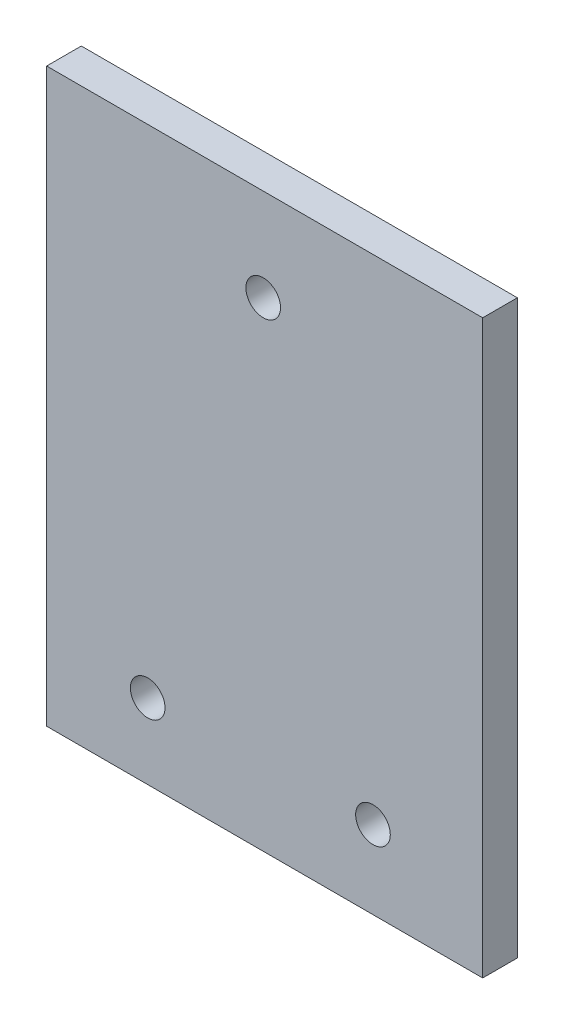
SolidWorks part; units mm, degrees
ref_plane "Front Plane" through (0, 0, 0) normal (0, 0, 1) x (1, 0, 0)
ref_plane "Top Plane" through (0, 0, 0) normal (0, 1, 0) x (1, 0, 0)
ref_plane "Right Plane" through (0, 0, 0) normal (1, 0, 0) x (0, 0, -1)
sketch "Sketch1" plane through (0, 0, 0) normal (0, 0, 1) x (1, 0, 0)
  line L1 (0, 0) -> (151, 0)
  line L2 (0, 0) -> (0, -198)
  line L3 (0, -198) -> (151, -198)
  line L4 (151, 0) -> (151, -198)
  dimension "D1" = 198
  dimension "D2" = 151
extrude "Boss-Extrude1" add sketch "Sketch1" along normal blind 12
sketch "Sketch2" plane through (0, 0, 12) normal (0, 0, 1) x (1, 0, 0)
  line L0 (151, -198) -> (151, 0) construction
  circle A0 centre (75, -32) radius 6
  circle A1 centre (35, -172) radius 6
  circle A2 centre (113, -171) radius 6
  point P6 (31.226, -162.6439)
  point P7 (0, 0)
  point P8 (35.6874, -160.818)
  point P14 (0, 0)
  point P16 (81.7441, 17.8722)
  dimension "D1" = 35
  dimension "D7" = 12
  dimension "D2" = 26
  dimension "D3" = 38
  dimension "D4" = 27
  dimension "D5" = 32
  dimension "D6" = 75
extrude "Cut-Extrude1" cut sketch "Sketch2" against normal blind 12
